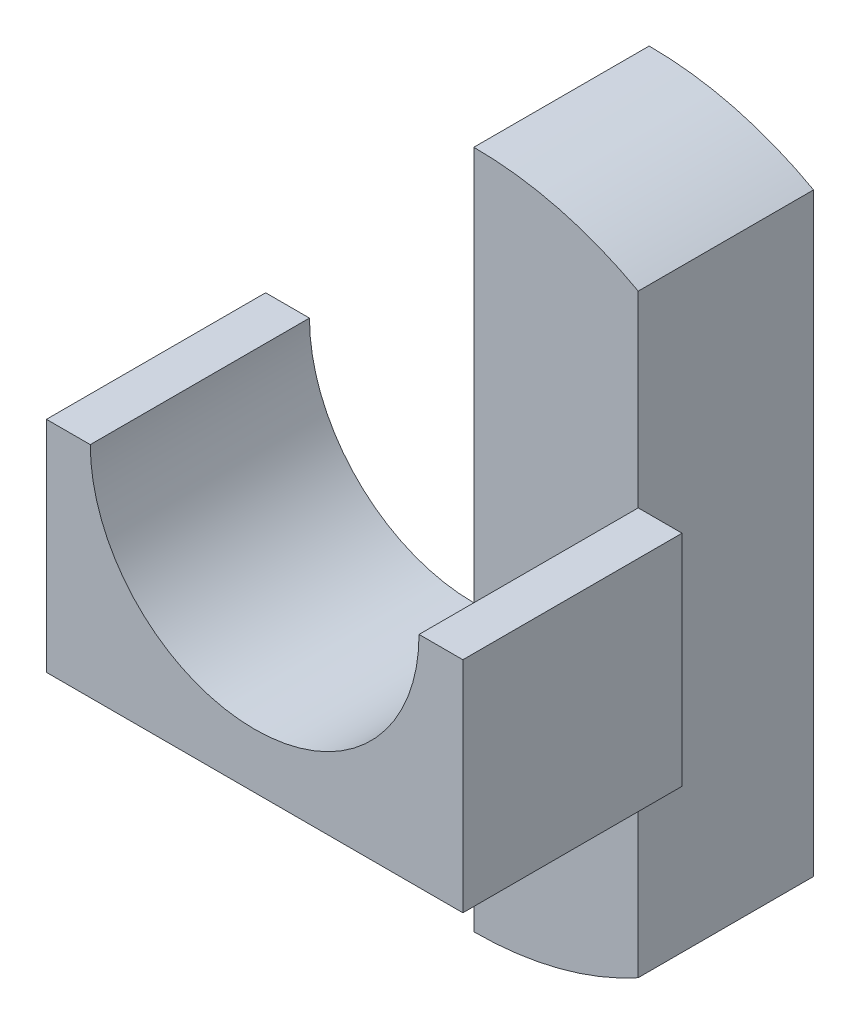
SolidWorks part; units mm, degrees
ref_plane "前视基准面" through (0, 0, 0) normal (0, 0, 1) x (1, 0, 0)
ref_plane "上视基准面" through (0, 0, 0) normal (0, 1, 0) x (1, 0, 0)
ref_plane "右视基准面" through (0, 0, 0) normal (1, 0, 0) x (0, 0, -1)
sketch "草图1" plane through (0, 0, 0) normal (0, 0, 1) x (1, 0, 0)
  line L0 (7.5, -13.5647) -> (7.5, 13.5647)
  line L1 (0, 15.5) -> (0, -15.5)
  arc A1 (7.5, -13.5647) -> (0, -15.5) centre (0, 0) cw
  arc A2 (0, 15.5) -> (7.5, 13.5647) centre (0, 0) cw
  point P0 (0, 0)
extrude "凸台-拉伸1" add sketch "草图1" along normal blind 8
sketch "草图3" plane through (0, 0, 8) normal (0, 0, 1) x (1, 0, 0)
  line L0 (0, 15.5) -> (0, -15.5) construction
  line L1 (-7.5, -2.5) -> (-7.5, -5)
  line L2 (7.5, -5) -> (9.5, -5)
  line L4 (7.5, -13.5647) -> (7.5, 13.5647) construction
  line L6 (-7.5, 13.5647) -> (-7.5, -13.5647) construction
  line L7 (-7.5, -2.5) -> (-7.5, 5)
  line L8 (7.5, -2.5) -> (7.5, 5)
  line L9 (9.5, -5) -> (9.5, 5)
  line L10 (7.5, -2.5) -> (7.5, -5)
  line L11 (7.5, -5) -> (-7.5, -5)
  line L12 (9.5, 5) -> (7.5, 5)
  line L13 (-7.5, -5) -> (-9.5, -5)
  line L14 (-9.5, -5) -> (-9.5, 5)
  line L15 (-9.5, 5) -> (-7.5, 5)
  arc A0 (-7.5, 5) -> (7.5, 5) centre (0, 5) ccw
  point P2 (-7.5, 5)
  point P5 (7.5, 5)
  line M11 (7.5, -13.5647) -> (7.5, 13.5647)
  line M13 (0, 15.5) -> (0, -15.5)
  dimension "D1" = 15
  dimension "D2" = 5
  dimension "D3" = 10
  dimension "D4" = 2
extrude "凸台-拉伸2" add sketch "草图3" along normal blind 10 contours L9 L12 L2 M11 | A0 L11 M13 M11 | A0 L7 L1 L11 M13 | L15 L14 L13 L1 L7
